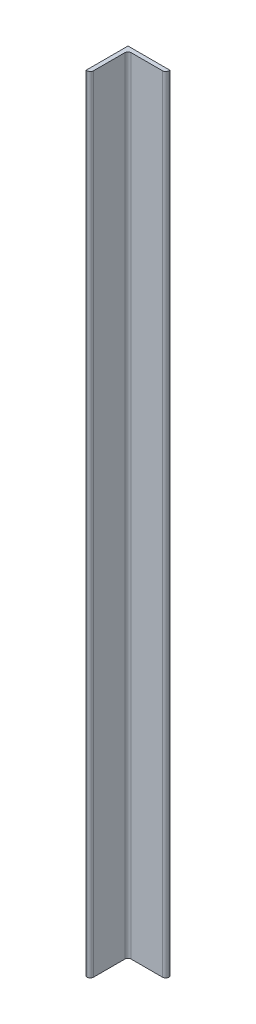
SolidWorks part; units mm, degrees
material "ASTM A36 Steel"
ref_plane "Front Plane" through (0, 0, 0) normal (0, 0, 1) x (1, 0, 0)
ref_plane "Top Plane" through (0, 0, 0) normal (0, 1, 0) x (1, 0, 0)
ref_plane "Right Plane" through (0, 0, 0) normal (1, 0, 0) x (0, 0, -1)
sketch "Sketch1" plane through (0, 0, 0) normal (0, 1, 0) x (1, 0, 0)
  line L0 (-27.4999, 29.2132) -> (-67.4999, 29.2132)
  line L1 (-67.4999, 29.2132) -> (-67.4999, -10.7868)
  line L2 (-67.4999, -10.7868) -> (-66.4999, -10.7868)
  line L3 (-63.4999, -7.7868) -> (-63.4999, 22.2132)
  line L4 (-60.4999, 25.2132) -> (-30.4999, 25.2132)
  line L5 (-27.4999, 28.2132) -> (-27.4999, 29.2132)
  arc A0 (-66.4999, -10.7868) -> (-63.4999, -7.7868) centre (-66.4999, -7.7868) ccw
  arc A1 (-63.4999, 22.2132) -> (-60.4999, 25.2132) centre (-60.4999, 22.2132) cw
  arc A2 (-30.4999, 25.2132) -> (-27.4999, 28.2132) centre (-30.4999, 28.2132) ccw
  point P8 (-63.4999, -10.7868)
  point P13 (-27.4999, 25.2132)
  dimension "D5" = 3
  dimension "D1" = 40
  dimension "D2" = 40
  dimension "D3" = 4
  dimension "D4" = 4
extrude "Boss-Extrude1" add sketch "Sketch1" along normal blind 750
